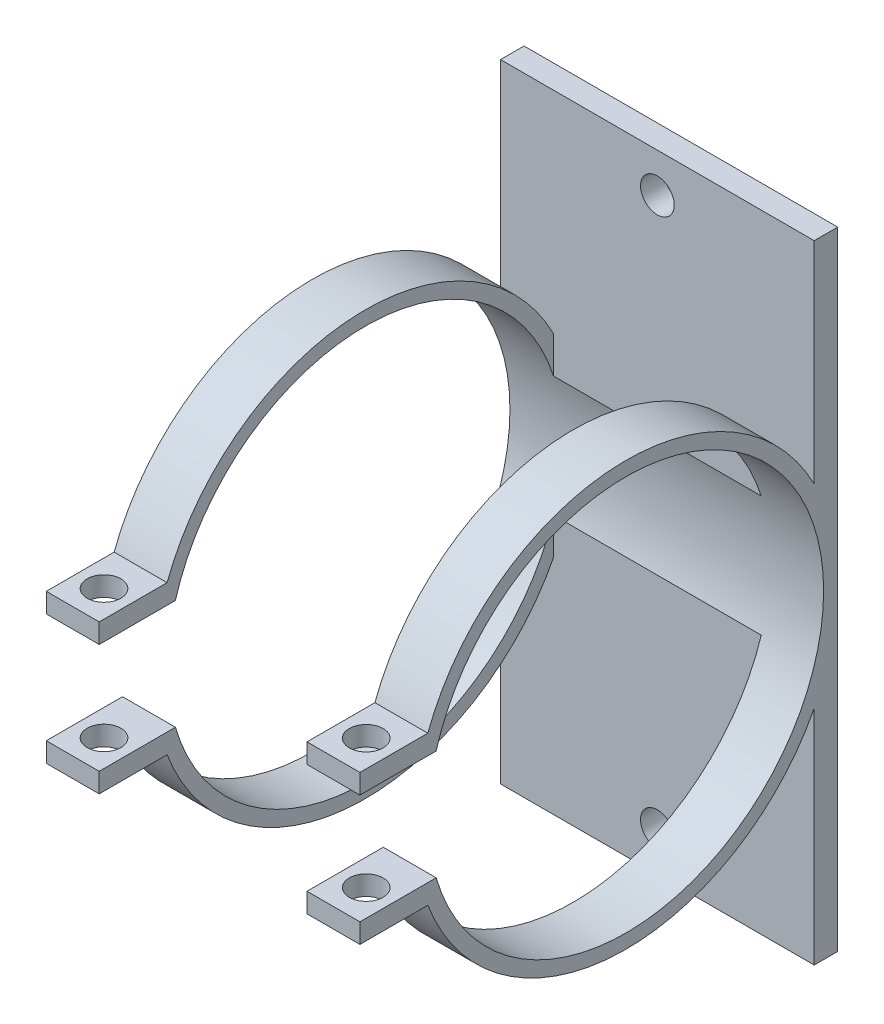
SolidWorks part; units mm, degrees
ref_plane "Front Plane" through (0, 0, 0) normal (0, 0, 1) x (1, 0, 0)
ref_plane "Top Plane" through (0, 0, 0) normal (0, 1, 0) x (1, 0, 0)
ref_plane "Right Plane" through (0, 0, 0) normal (1, 0, 0) x (0, 0, -1)
sketch "Sketch1" plane through (0, 0, 0) normal (0, 0, 1) x (1, 0, 0)
  line L1 (0, 0) -> (40, 0)
  line L2 (0, 0) -> (0, 80)
  line L3 (0, 80) -> (40, 80)
  line L4 (40, 0) -> (40, 80)
  circle A0 centre (20, 75) radius 2.15
  circle A1 centre (20, 5) radius 2.15
  point P9 (12.5, 54.0819)
  point P10 (20.2035, 75)
  point P11 (0, 0)
  dimension "D2" = 4.3
  dimension "D3" = 4.3
  dimension "D1" = 40
  dimension "D4" = 80
  dimension "D5" = 5
  dimension "D6" = 5
  dimension "D7" = 20
extrude "Boss-Extrude1" add sketch "Sketch1" along normal blind 3
sketch "Sketch2" plane through (0, 0, 0) normal (-1, 0, 0) x (0, 0, 1)
  line L0 (0, 80) -> (0, 0) construction
  line L1 (27, 40.7428) -> (71.6863, 40.7428) construction
  line L2 (51.2083, 47.7428) -> (60.9319, 47.7428)
  line L3 (60.9319, 47.7428) -> (60.9319, 50.2428)
  line L4 (60.9319, 50.2428) -> (52.2735, 50.2428)
  line L5 (51.2083, 33.7428) -> (60.9319, 33.7428)
  line L6 (60.9319, 33.7428) -> (60.9319, 31.2428)
  line L7 (60.9319, 31.2428) -> (52.2735, 31.2428)
  arc A0 (51.2083, 47.7428) -> (51.2083, 33.7428) centre (27, 40.7428) ccw
  arc A1 (52.2735, 50.2428) -> (52.2735, 31.2428) centre (27, 40.7428) ccw
  point P12 (60.8924, 42.4064)
  point P15 (60.8989, 38.8973)
  dimension "D1" = 50.4
  dimension "D2" = 54
  dimension "D3" = 2.5
  dimension "D4" = 2.5
  dimension "D5" = 7
  dimension "D6" = 7
extrude "Boss-Extrude2" add sketch "Sketch2" against normal up to surface (40 mm away) up to face at (40, 40, 1.5)
sketch "Sketch3" plane through (0, 0, 0) normal (-1, 0, 0) x (0, 0, 1)
  circle A0 centre (27, 40.7428) radius 25.2
extrude "Cut-Extrude1" cut sketch "Sketch3" against normal up to surface (40 mm away) up to face at (40, 40.5571, 29.4415)
sketch "Sketch5" plane through (0, 0, 60.9319) normal (0, 0, 1) x (1, 0, 0)
  line L0 (40, 67.7428) -> (0, 67.7428) construction
  line L1 (6.75, 67.7428) -> (33.25, 67.7428)
  line L2 (6.75, 67.7428) -> (6.75, 13.7428)
  line L3 (6.75, 13.7428) -> (33.25, 13.7428)
  line L4 (33.25, 67.7428) -> (33.25, 13.7428)
  line L5 (0, 13.7428) -> (40, 13.7428) construction
  line L6 (0, 67.7428) -> (0, 50.2428) construction
  line L7 (40, 50.2428) -> (40, 67.7428) construction
  dimension "D1" = 6.75
  dimension "D2" = 6.75
extrude "Cut-Extrude2" cut sketch "Sketch5" against normal up to surface (57.9319 mm away) up to face at (20, 66.5561, 3)
sketch "Sketch6" plane through (0, 50.2428, 0) normal (0, 1, 0) x (1, 0, 0)
  circle A0 centre (3.375, -56.9408) radius 2.15
  circle A1 centre (21.625, -56.9408) radius 2.15
  dimension "D1" = 4.3
  dimension "D2" = 4.3
extrude "Cut-Extrude3" cut sketch "Sketch6" against normal through all
sketch "Sketch7" plane through (0, 50.2428, 0) normal (0, 1, 0) x (1, 0, 0)
  circle A0 centre (36.625, -56.7542) radius 2.15
  dimension "D1" = 4.3
extrude "Cut-Extrude4" cut sketch "Sketch7" against normal through all
